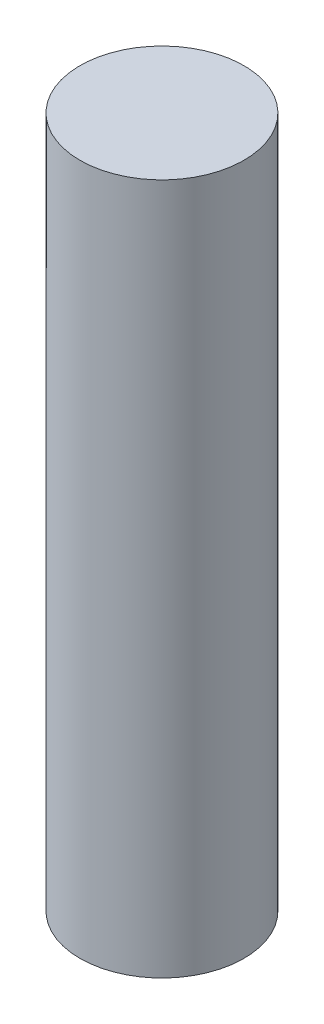
SolidWorks part; units mm, degrees
ref_plane "Front Plane" through (0, 0, 0) normal (0, 0, 1) x (1, 0, 0)
ref_plane "Top Plane" through (0, 0, 0) normal (0, 1, 0) x (1, 0, 0)
ref_plane "Right Plane" through (0, 0, 0) normal (1, 0, 0) x (0, 0, -1)
sketch "Sketch1" plane through (0, 0, 0) normal (0, 1, 0) x (1, 0, 0)
  circle A0 centre (0, 0) radius 350
extrude "Boss-Extrude1" add sketch "Sketch1" along normal blind 2950
